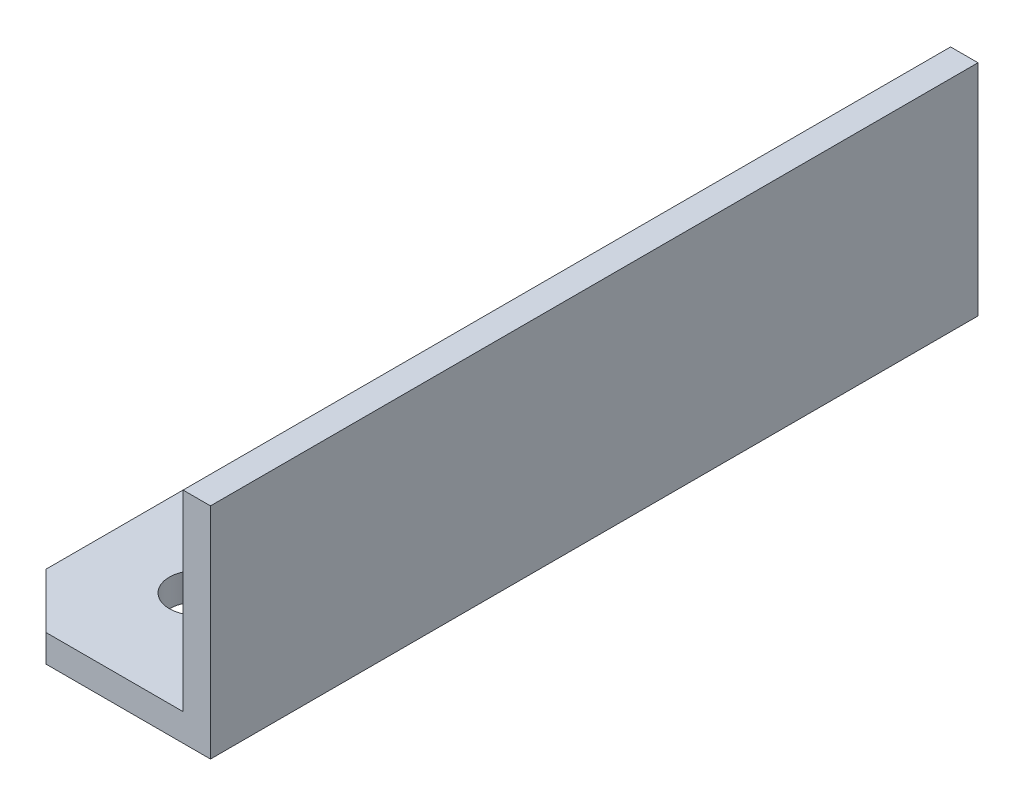
SolidWorks part; units mm, degrees
ref_plane "Front" through (0, 0, 0) normal (0, 0, 1) x (1, 0, 0)
ref_plane "Top" through (0, 0, 0) normal (0, 1, 0) x (1, 0, 0)
ref_plane "Right" through (0, 0, 0) normal (1, 0, 0) x (0, 0, -1)
sketch "Sketch1" plane through (0, 0, 0) normal (0, 0, 1) x (1, 0, 0)
  line L0 (-40, 0) -> (0, 0)
  line L1 (0, 0) -> (0, 40)
  dimension "D1" = 40
  dimension "D2" = 40
extrude "Extrude-Thin1" add sketch "Sketch1" along normal blind 70 and the other way blind 70 thin thin type one direction reverse wall 5
chamfer "Chamfer1" distance 10 angle 45 2 edges at (-40, 2.5, -70) (-40, 2.5, 70)
sketch "Sketch2" plane through (0, 5, 0) normal (0, 1, 0) x (1, 0, 0)
  line L1 (-40, 60) -> (-40, -60) construction
  circle A0 centre (-22.5, 50) radius 5
  circle A1 centre (-22.5, -50) radius 5
  dimension "D1" = 10
  dimension "D2" = 10
  dimension "D3" = 100
  dimension "D4" = 50
  dimension "D5" = 17.5
  dimension "D6" = 17.5
extrude "Cut-Extrude1" cut sketch "Sketch2" against normal blind 10
